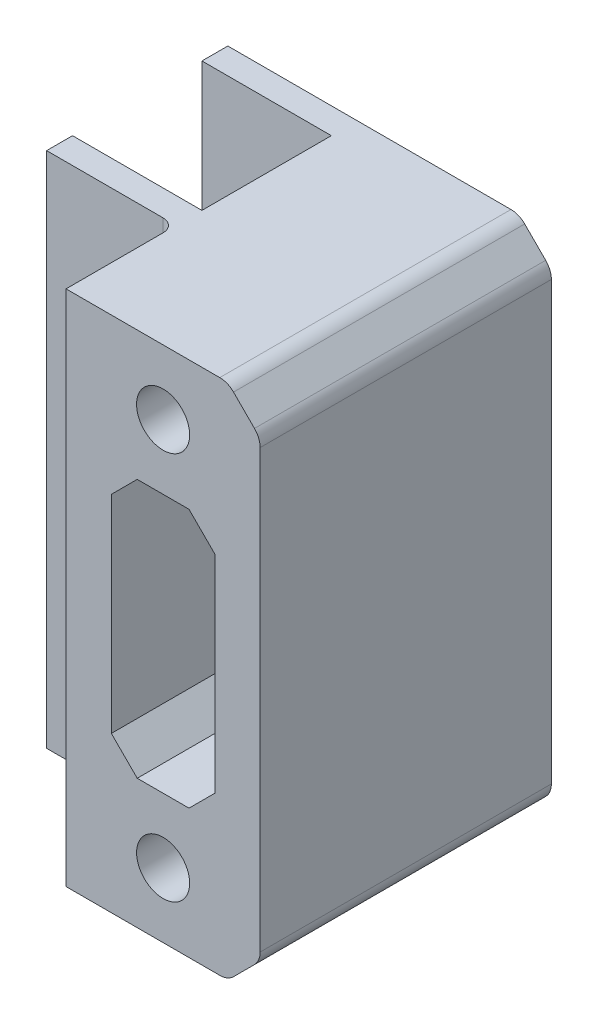
SolidWorks part; units mm, degrees
material "ABS"
ref_plane "Alzado" through (0, 0, 0) normal (0, 0, 1) x (1, 0, 0)
ref_plane "Planta" through (0, 0, 0) normal (0, 1, 0) x (1, 0, 0)
ref_plane "Vista lateral" through (0, 0, 0) normal (1, 0, 0) x (0, 0, -1)
sketch "Croquis1" plane through (0, 0, 0) normal (0, 0, 1) x (1, 0, 0)
  line L0 (14.1213, 35.8787) -> (10.8787, 39.1213)
  line L1 (8.7574, 40) -> (-15, 40)
  line L2 (-15, 40) -> (-15, -40)
  line L3 (-15, -40) -> (8.7574, -40)
  line L4 (10.8787, -39.1213) -> (14.1213, -35.8787)
  line L5 (15, -33.7574) -> (15, 33.7574)
  line L6 (-4, -20) -> (-8, -16)
  line L7 (-4, -20) -> (4, -20)
  line L8 (8, -16) -> (4, -20)
  line L9 (8, -16) -> (8, 16)
  line L10 (4, 20) -> (8, 16)
  line L11 (4, 20) -> (-4, 20)
  line L12 (-8, 16) -> (-4, 20)
  line L13 (-8, 16) -> (-8, -16)
  line L14 (8.7574, 37) -> (13, 37) construction
  line L15 (0, 30) -> (8.7574, 30) construction
  circle A0 centre (0, 30) radius 4.1
  circle A1 centre (0, -30) radius 4.1
  arc A2 (10.8787, 39.1213) -> (8.7574, 40) centre (8.7574, 37) ccw
  arc A3 (8.7574, -40) -> (10.8787, -39.1213) centre (8.7574, -37) ccw
  arc A4 (14.1213, -35.8787) -> (15, -33.7574) centre (12, -33.7574) ccw
  arc A5 (15, 33.7574) -> (14.1213, 35.8787) centre (12, 33.7574) ccw
  point P26 (-8, 0)
  point P27 (-15, 0)
  dimension "D8" = 3
  dimension "D9" = 8.2
  dimension "D21" = 8.2
  dimension "D25" = 3
  dimension "D26" = 3
  dimension "D1" = 16
  dimension "D2" = 40
  dimension "D3" = 8
  dimension "D4" = 32
  dimension "D5" = 80
  dimension "D6" = 30
  dimension "D10" = 15
  dimension "D11" = 10
  dimension "D12" = 10
  dimension "D13" = 8
  dimension "D14" = 4
  dimension "D15" = 20
  dimension "D16" = 16
  dimension "D17" = 8
  dimension "D18" = 4
  dimension "D19" = 20
  dimension "D20" = 8
  dimension "D22" = 15
  dimension "D23" = 6.2426
  dimension "D24" = 3.2426
  dimension "D27" = 4.5858
  dimension "D28" = 6.2426
extrude "Saliente-Extruir1" add sketch "Croquis1" along normal mid plane 45
sketch "Croquis2" plane through (0, 40, 0) normal (0, 1, 0) x (1, 0, 0)
  line L8 (-15, -22.5) -> (-15, 22.5) construction
  line L9 (-15, 22.5) -> (-35, 22.5)
  line L10 (-15, 22.5) -> (-15, 18.5)
  line L11 (-15, 18.5) -> (-35, 18.5)
  line L12 (-35, 22.5) -> (-35, 18.5)
  line L13 (-15, -5.5) -> (-35, -5.5)
  line L14 (-15, -5.5) -> (-15, -1.5)
  line L15 (-15, -1.5) -> (-35, -1.5)
  line L16 (-35, -5.5) -> (-35, -1.5)
  dimension "D3" = 4
  dimension "D1" = 20
  dimension "D2" = 4
  dimension "D4" = 20
extrude "Saliente-Extruir2" add sketch "Croquis2" against normal up to vertex (80 mm away)
fillet "Redondeo1" radius 2 1 edges at (-15, 0, 5.5)
sketch "Croquis3" plane through (0, 0, -22.5) normal (0, 0, -1) x (-1, 0, 0)
  circle A0 centre (0, -30) radius 4.1 construction
  circle A1 centre (0, -30) radius 4.1
  circle A2 centre (0, 30) radius 4.1 construction
  circle A3 centre (0, 30) radius 4.1
extrude "Saliente-Extruir3" add sketch "Croquis3" against normal blind 25
